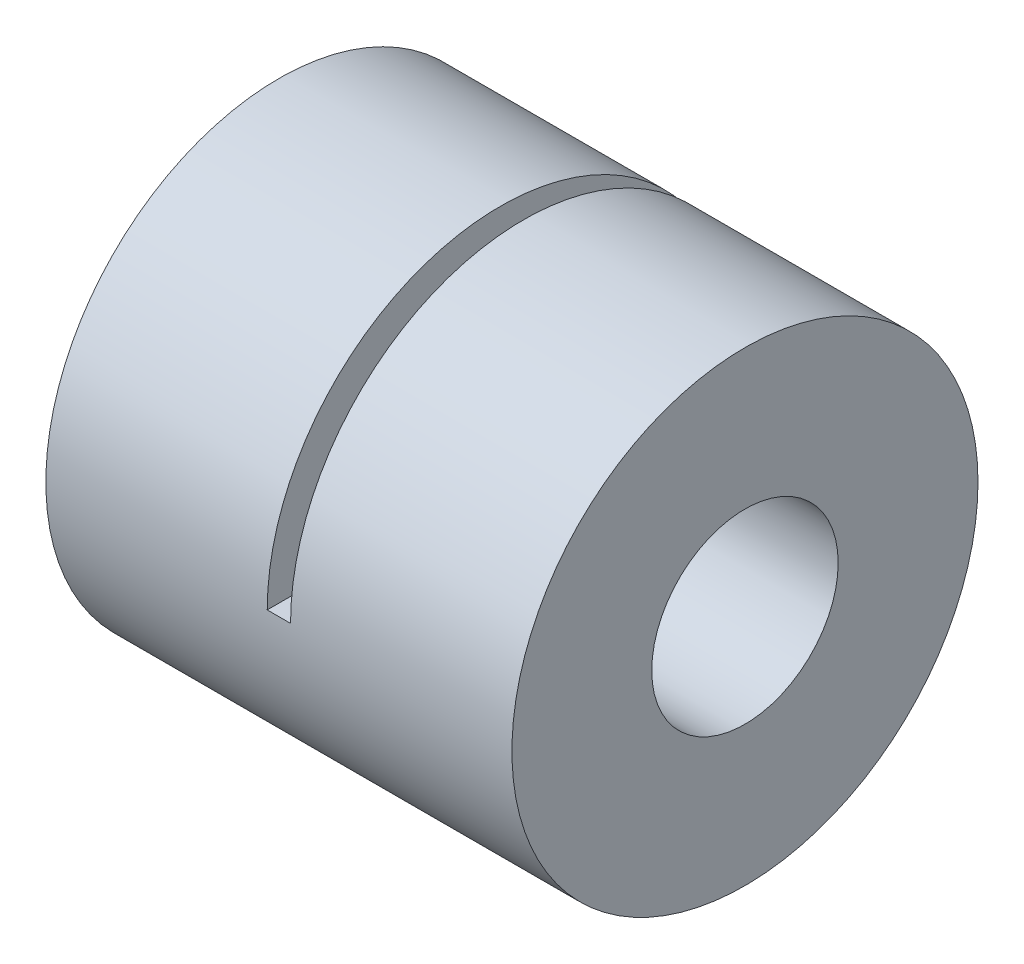
SolidWorks part; units mm, degrees
ref_plane "正面" through (0, 0, 0) normal (0, 0, 1) x (1, 0, 0)
ref_plane "平面" through (0, 0, 0) normal (0, 1, 0) x (1, 0, 0)
ref_plane "右側面" through (0, 0, 0) normal (1, 0, 0) x (0, 0, -1)
sketch "ｽｹｯﾁ1" plane through (0, 0, 0) normal (1, 0, 0) x (0, 0, -1)
  circle A0 centre (0, 0) radius 10
  circle A1 centre (0, 0) radius 4
  dimension "D1" = 20
  dimension "D2" = 8
extrude "ﾎﾞｽ - 押し出し1" add sketch "ｽｹｯﾁ1" along normal blind 20
sketch "ｽｹｯﾁ2" plane through (0, 0, 0) normal (0, 1, 0) x (1, 0, 0)
  line L0 (10, 10) -> (0, 0) construction
  line L1 (20, 10) -> (0, 10) construction
  line L2 (0, 0) -> (10, -10) construction
  line L3 (0, -10) -> (20, -10) construction
  line L4 (10, -10) -> (20, 0) construction
  line L5 (20, -10) -> (20, 10) construction
  line L6 (20, 0) -> (10, 10) construction
  line L7 (10, 10) -> (0, -10) construction
  line L8 (0, -10) -> (20, -10) construction
  line L9 (20, -10) -> (0, 10) construction
  line L10 (0, 10) -> (10, -10) construction
  line L11 (10, -10) -> (20, 10) construction
  line L12 (20, 10) -> (20, -10) construction
  line L13 (20, -10) -> (10, 10) construction
  line L14 (10, 10) -> (0, 10) construction
  line L15 (0, 10) -> (0, -10) construction
  line L16 (0, -10) -> (20, 10) construction
  line L18 (10.5, -10) -> (9.5, -10)
  line L19 (10.5, -10) -> (10.5, 10)
  line L20 (10.5, 10) -> (9.5, 10)
  line L21 (9.5, -10) -> (9.5, 10)
  line L22 (10.5, -10) -> (9.5, 10) construction
  line L23 (10.5, 10) -> (9.5, -10) construction
  point P17 (10, 0)
  dimension "D1" = 1
extrude "ｶｯﾄ - 押し出し1" cut sketch "ｽｹｯﾁ2" along normal through all
